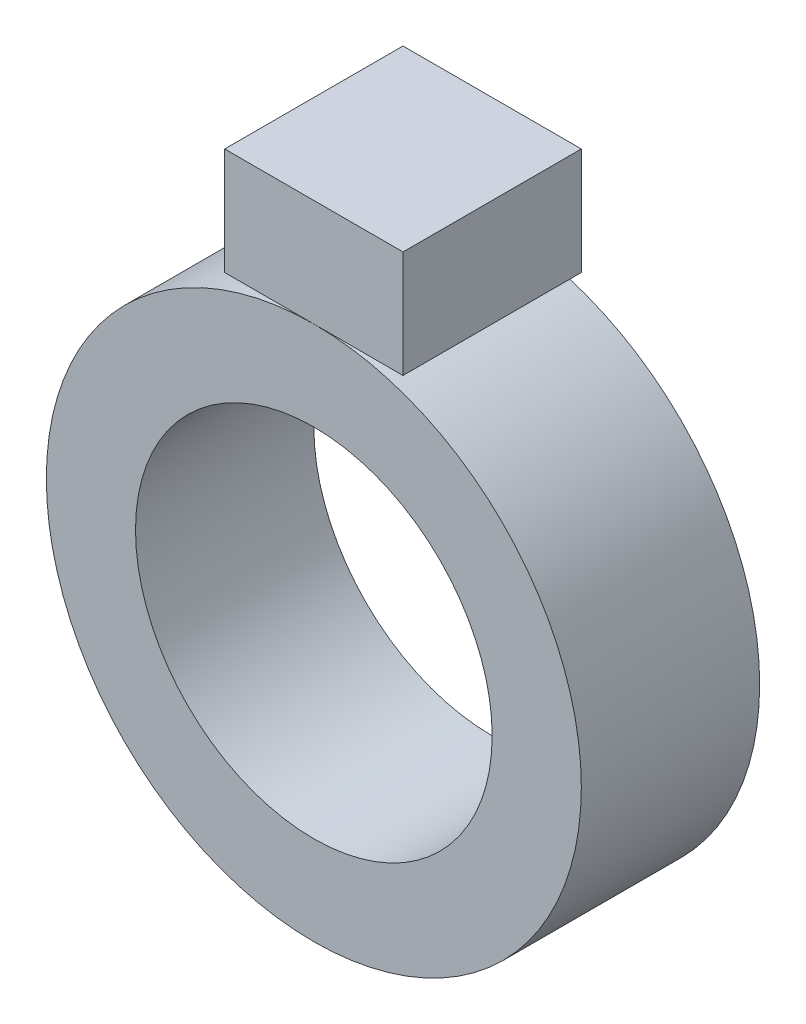
SolidWorks part; units mm, degrees
ref_plane "Front Plane" through (0, 0, 0) normal (0, 0, 1) x (1, 0, 0)
ref_plane "Top Plane" through (0, 0, 0) normal (0, 1, 0) x (1, 0, 0)
ref_plane "Right Plane" through (0, 0, 0) normal (1, 0, 0) x (0, 0, -1)
sketch "Sketch1" plane through (0, 0, 0) normal (0, 0, 1) x (1, 0, 0)
  circle A0 centre (0, 0) radius 5
  circle A1 centre (0, 0) radius 7.5
  dimension "D1" = 10
  dimension "D2" = 15
extrude "Boss-Extrude1" add sketch "Sketch1" along normal blind 5
ref_plane "Plane1" through (0, 7.5, 0) normal (0, 1, 0) x (1, 0, 0)
sketch "Sketch2" plane through (0, 7.5, 0) normal (0, 1, 0) x (1, 0, 0)
  line L0 (0, 0) -> (0, -5) construction
  line L1 (0, -2.5) -> (-9.3419, -2.5) construction
  line L2 (-9.3419, -2.5) -> (8.3924, -2.5) construction
  line L3 (7.5, 0) -> (-7.5, 0) construction
  line L5 (-2.5, -5) -> (2.5, -5)
  line L6 (-2.5, -5) -> (-2.5, 0)
  line L7 (-2.5, 0) -> (2.5, 0)
  line L8 (2.5, -5) -> (2.5, 0)
  line L9 (-2.5, -5) -> (2.5, 0) construction
  line L10 (-2.5, 0) -> (2.5, -5) construction
  dimension "D1" = 2.5
  dimension "D2" = 5
  dimension "D3" = 5
extrude "Boss-Extrude2" add sketch "Sketch2" along normal blind 3 separate body
